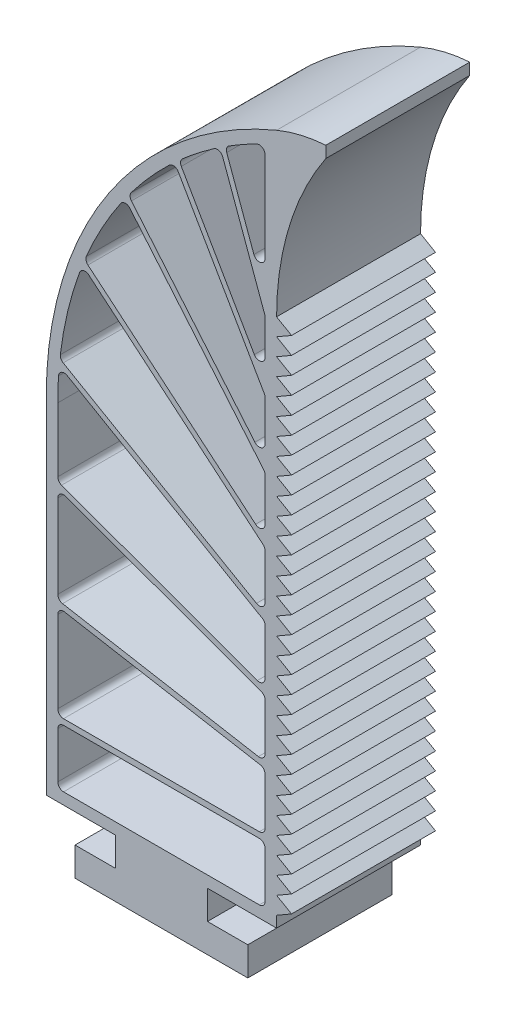
SolidWorks part; units mm, degrees
ref_plane "Front Plane" through (0, 0, 0) normal (0, 0, 1) x (1, 0, 0)
ref_plane "Top Plane" through (0, 0, 0) normal (0, 1, 0) x (1, 0, 0)
ref_plane "Right Plane" through (0, 0, 0) normal (1, 0, 0) x (0, 0, -1)
sketch "Sketch2" plane through (0, 0, 0) normal (0, 0, 1) x (1, 0, 0)
  line L0 (-15, 0) -> (15, 0)
  line L1 (15, 0) -> (15, 5)
  line L2 (15, 5) -> (8, 5)
  line L3 (8, 5) -> (8, 10)
  line L4 (8, 10) -> (20, 10)
  line L5 (20, 10) -> (20, 130)
  line L6 (-15, 0) -> (-15, 5)
  line L7 (-15, 5) -> (-8, 5)
  line L8 (-8, 5) -> (-8, 10)
  line L9 (-8, 10) -> (-20, 10)
  line L10 (-20, 10) -> (-20, 70)
  arc A0 (20, 130) -> (-20, 70) centre (45, 70) ccw
  dimension "D1" = 30
  dimension "D2" = 5
  dimension "D3" = 5
  dimension "D4" = 40
  dimension "D5" = 120
  dimension "D6" = 60
  dimension "D7" = 16
extrude "Boss-Extrude1" add sketch "Sketch2" along normal blind 25
sketch "Sketch3" plane through (0, 0, 25) normal (0, 0, 1) x (1, 0, 0)
  line L0 (-18, 12) -> (18, 12)
  line L1 (18, 12) -> (18, 22)
  line L2 (18, 22) -> (-18, 22)
  line L3 (-18, 22) -> (-18, 12)
  line L4 (-20, 70) -> (-20, 10) construction
  line L5 (20, 10) -> (20, 130) construction
  line L6 (8, 10) -> (20, 10) construction
  dimension "D1" = 2
  dimension "D2" = 2
  dimension "D3" = 2
  dimension "D4" = 10
sketch "Sketch4" plane through (0, 0, 25) normal (0, 0, 1) x (1, 0, 0)
  line L0 (-18, 23) -> (18, 23)
  line L1 (18, 23) -> (18, 33)
  line L2 (18, 33) -> (-18, 39.3478)
  line L3 (-18, 39.3478) -> (-18, 23)
  line L4 (-20, 70) -> (-20, 10) construction
  line L5 (18, 22) -> (-18, 22) construction
  line L6 (20, 10) -> (20, 130) construction
  dimension "D1" = 2
  dimension "D2" = 1
  dimension "D3" = 2
  dimension "D4" = 10
  dimension "D5" = 10
sketch "Sketch5" plane through (0, 0, 25) normal (0, 0, 1) x (1, 0, 0)
  line L0 (-18, 40.3632) -> (18, 34.0154)
  line L1 (18, 34.0154) -> (18, 44.0154)
  line L2 (18, 44.0154) -> (-18, 57.1184)
  line L3 (-18, 57.1184) -> (-18, 40.3632)
  line L4 (-20, 70) -> (-20, 10) construction
  line L5 (20, 10) -> (20, 130) construction
  line L7 (18, 33) -> (-18, 39.3478) construction
  line L8 (-18, 23) -> (18, 23) construction
  dimension "D1" = 2
  dimension "D2" = 2
  dimension "D3" = 1
  dimension "D4" = 20
  dimension "D5" = 10
sketch "Sketch6" plane through (0, 0, 25) normal (0, 0, 1) x (1, 0, 0)
  line L0 (-18, 58.1825) -> (18, 45.0796)
  line L1 (18, 45.0796) -> (18, 55.0796)
  line L2 (18, 55.0796) -> (-17.7403, 75.7143)
  line L3 (-18, 58.1825) -> (-18, 70)
  line L5 (18, 44.0154) -> (-18, 57.1184) construction
  line L6 (-20, 70) -> (-20, 10) construction
  line L7 (20, 10) -> (20, 130) construction
  line L8 (-18, 23) -> (18, 23) construction
  line L9 (-17.6313, 76.806) -> (18, 56.2343)
  line L10 (18, 56.2343) -> (18, 66.2343)
  line L11 (18, 66.2343) -> (-13.7124, 92.8442)
  arc A0 (-17.7403, 75.7143) -> (-18, 70) centre (45, 70) ccw
  arc A2 (20, 130) -> (-20, 70) centre (45, 70) ccw construction
  arc A3 (-13.7124, 92.8442) -> (-17.6313, 76.806) centre (45, 70) ccw
  dimension "D1" = 1
  dimension "D7" = 1
  dimension "D8" = 10
  dimension "D2" = 2
  dimension "D3" = 2
  dimension "D4" = 30
  dimension "D5" = 10
  dimension "D6" = 0
  dimension "D9" = 40
sketch "Sketch7" plane through (0, 0, 25) normal (0, 0, 1) x (1, 0, 0)
  line L0 (-13.3224, 93.8223) -> (18, 67.5397)
  line L1 (18, 67.5397) -> (18, 77.5397)
  line L2 (18, 77.5397) -> (-6.3269, 106.5314)
  line L3 (18, 66.2343) -> (-13.7124, 92.8442) construction
  line L4 (18, 56.2343) -> (18, 66.2343) construction
  arc A0 (-6.3269, 106.5314) -> (-13.3224, 93.8223) centre (45, 70) ccw
  arc A1 (-13.7124, 92.8442) -> (-17.6313, 76.806) centre (45, 70) ccw construction
  dimension "D1" = 1
  dimension "D2" = 10
  dimension "D3" = 10
sketch "Sketch8" plane through (0, 0, 25) normal (0, 0, 1) x (1, 0, 0)
  line L0 (-5.7222, 107.3665) -> (18, 79.0954)
  line L1 (18, 79.0954) -> (18, 89.0954)
  line L2 (18, 89.0954) -> (2.2875, 116.3103)
  line L3 (18, 67.5397) -> (18, 77.5397) construction
  line L4 (18, 77.5397) -> (-6.3269, 106.5314) construction
  arc A0 (2.2875, 116.3103) -> (-5.7222, 107.3665) centre (45, 70) ccw
  arc A1 (-6.3269, 106.5314) -> (-13.3224, 93.8223) centre (45, 70) ccw construction
  dimension "D1" = 10
  dimension "D2" = 1
  dimension "D3" = 10
  dimension "10" = 10
sketch "Sketch9" plane through (0, 0, 25) normal (0, 0, 1) x (1, 0, 0)
  line L0 (3.0452, 116.9978) -> (18, 91.0954)
  line L1 (18, 91.0954) -> (18, 101.0954)
  line L2 (18, 101.0954) -> (10.2028, 122.5181)
  line L3 (18, 79.0954) -> (18, 89.0954) construction
  line L4 (18, 89.0954) -> (2.2875, 116.3103) construction
  arc A0 (10.2028, 122.5181) -> (3.0452, 116.9978) centre (45, 70) ccw
  arc A1 (2.2875, 116.3103) -> (-5.7222, 107.3665) centre (45, 70) ccw construction
  dimension "D1" = 1
  dimension "D2" = 10
  dimension "D3" = 10
sketch "Sketch10" plane through (0, 0, 25) normal (0, 0, 1) x (1, 0, 0)
  line L0 (11.0631, 123.0781) -> (18, 104.0192)
  line L1 (18, 104.0192) -> (18, 126.921)
  line L2 (18, 101.0954) -> (10.2028, 122.5181) construction
  line L3 (18, 91.0954) -> (18, 101.0954) construction
  arc A0 (18, 126.921) -> (11.0631, 123.0781) centre (45, 70) ccw
  arc A1 (10.2028, 122.5181) -> (3.0452, 116.9978) centre (45, 70) ccw construction
  dimension "D1" = 1
extrude "Cut-Extrude1" cut sketch "Sketch3" against normal through all contours L0 L1 L2 L3
extrude "Cut-Extrude2" cut sketch "Sketch4" against normal through all contours L0 L1 L2 L3
extrude "Cut-Extrude3" cut sketch "Sketch5" against normal through all contours L0 L1 L2 L3
extrude "Cut-Extrude4" cut sketch "Sketch6" against normal through all contours L0 L1 L2 A0 L3
sketch "Sketch12" plane through (0, 0, 25) normal (0, 0, 1) x (1, 0, 0)
  line L0 (-17.6313, 76.806) -> (18, 56.2343)
  line L1 (18, 56.2343) -> (18, 66.2343)
  line L2 (18, 66.2343) -> (-13.7124, 92.8442)
  line L3 (18, 55.0796) -> (-17.7403, 75.7143) construction
  line L4 (18, 45.0796) -> (18, 55.0796) construction
  line L5 (-13.3224, 93.8223) -> (18, 67.5397) construction
  arc A0 (-13.7124, 92.8442) -> (-17.6313, 76.806) centre (45, 70) ccw
  arc A1 (-17.7403, 75.7143) -> (-18, 70) centre (45, 70) ccw construction
  dimension "D1" = 1
  dimension "D2" = 1
extrude "Cut-Extrude5" cut sketch "Sketch12" against normal through all
extrude "Cut-Extrude6" cut sketch "Sketch7" against normal through all contours L0 L1 L2 A0
extrude "Cut-Extrude7" cut sketch "Sketch8" against normal through all contours L0 L1 L2 A0
extrude "Cut-Extrude8" cut sketch "Sketch9" against normal through all contours L0 L1 L2 A0
extrude "Cut-Extrude9" cut sketch "Sketch10" against normal through all contours L0 L1 A0
fillet "Fillet1" radius 1 35 edges at (18, 56.2343, 12.5) (18, 126.921, 12.5) (18, 101.0954, 12.5) (11.0631, 123.0781, 12.5) (3.0452, 116.9978, 12.5) (10.2028, 122.5181, 12.5) (18, 104.0192, 12.5) (18, 91.0954, 12.5) (18, 79.0954, 12.5) (18, 67.5397, 12.5) (-5.7222, 107.3665, 12.5) (-13.3224, 93.8223, 12.5) (-17.6313, 76.806, 12.5) (2.2875, 116.3103, 12.5) (-6.3269, 106.5314, 12.5) (-13.7124, 92.8442, 12.5) (18, 89.0954, 12.5) (18, 77.5397, 12.5) (18, 66.2343, 12.5) (18, 55.0796, 12.5) (-18, 58.1825, 12.5) (-17.7403, 75.7143, 12.5) (-18, 57.1184, 12.5) (-18, 40.3632, 12.5) (18, 44.0154, 12.5) (18, 33, 12.5) (18, 22, 12.5) (-18, 23, 12.5) (-18, 22, 12.5) (-18, 39.3478, 12.5) (18, 45.0796, 12.5) (18, 34.0154, 12.5) (18, 23, 12.5) (18, 12, 12.5) (-18, 12, 12.5)
sketch "Sketch13" plane through (0, 0, 25) normal (0, 0, 1) x (1, 0, 0)
  line L0 (20, 10) -> (20, 130) construction
  line L1 (28.5436, 132.0151) -> (28.5436, 130.0151)
  line L2 (20, 130) -> (20, 101.9347)
  arc A0 (20, 130) -> (28.5436, 132.0151) centre (30.3921, 105.059) cw
  arc A1 (20, 101.9347) -> (28.5436, 130.0151) centre (70.4182, 101.9347) cw
  arc A2 (20, 130) -> (-20, 70) centre (45, 70) ccw construction
  dimension "D1" = 2
extrude "Boss-Extrude2" add sketch "Sketch13" against normal up to surface (25 mm away) up to face at (15.3084, 119.3525, 0)
sketch "Sketch15" plane through (0, 0, 25) normal (0, 0, 1) x (1, 0, 0)
  line L0 (20, 101.9347) -> (22.5981, 100.4347)
  line L1 (22.5981, 100.4347) -> (20, 98.9347)
  line L2 (20, 10) -> (20, 101.9347) construction
  line L3 (20, 101.9347) -> (20, 98.9347)
  dimension "D1" = 3
  dimension "D2" = 3
  dimension "D3" = 3
extrude "Boss-Extrude3" add sketch "Sketch15" against normal up to surface (25 mm away) up to face at (15.3084, 119.3525, 0)
pattern_linear "LPattern1" count 30 spacing 3 along (0, -1, 0) of "Boss-Extrude3"
